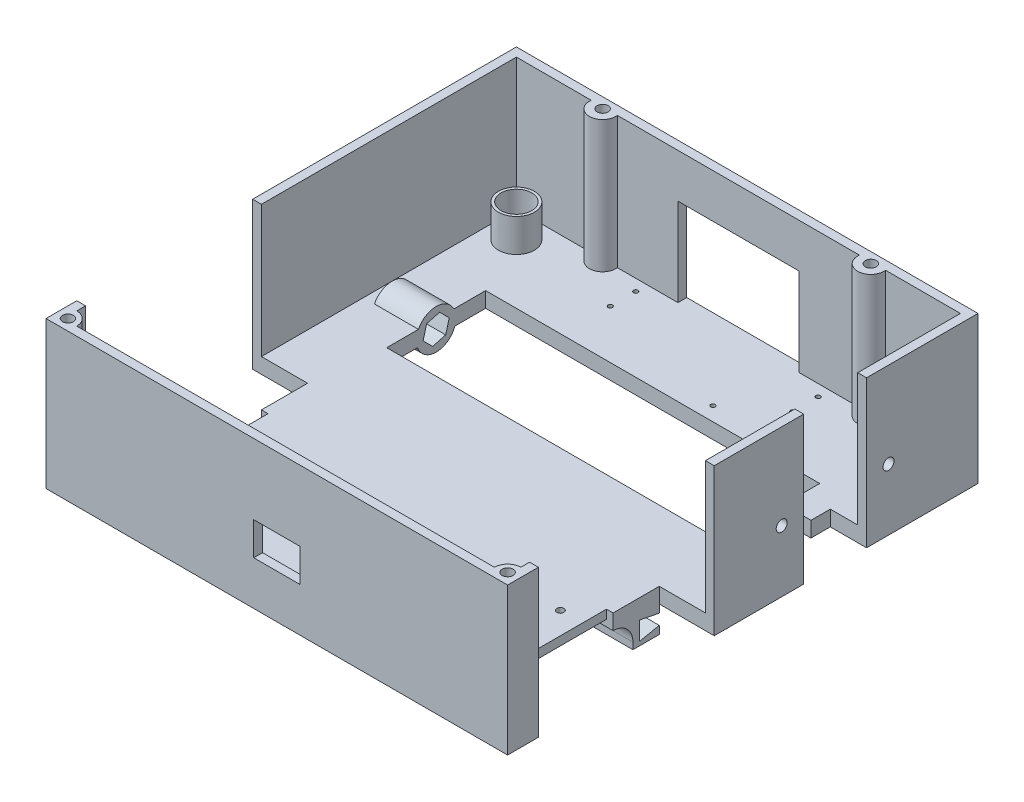
SolidWorks part; units mm, degrees
ref_plane "Front Plane" through (0, 0, 0) normal (0, 0, 1) x (1, 0, 0)
ref_plane "Top Plane" through (0, 0, 0) normal (0, 1, 0) x (1, 0, 0)
ref_plane "Right Plane" through (0, 0, 0) normal (1, 0, 0) x (0, 0, -1)
sketch "Sketch1" plane through (0, 0, 0) normal (0, 1, 0) x (1, 0, 0)
  line L1 (0, 0) -> (210, 0)
  line L2 (0, 0) -> (0, 214)
  line L3 (0, 214) -> (210, 214)
  line L4 (210, 0) -> (210, 214)
  dimension "D1" = 214
  dimension "D2" = 210
extrude "Boss-Extrude1" add sketch "Sketch1" along normal blind 7
sketch "Sketch2" plane through (0, 7, 0) normal (0, 1, 0) x (1, 0, 0)
  line L1 (0, 214) -> (210, 214)
  line L2 (0, 214) -> (0, 0)
  line L3 (0, 0) -> (210, 0)
  line L4 (210, 214) -> (210, 0)
  line L5 (206, 4) -> (4, 4)
  line L6 (206, 4) -> (206, 210)
  line L7 (206, 210) -> (4, 210)
  line L8 (4, 4) -> (4, 210)
  dimension "D1" = 4
  dimension "D2" = 4
  dimension "D3" = 4
  dimension "D4" = 4
extrude "Boss-Extrude2" add sketch "Sketch2" along normal blind 60
sketch "Sketch3" plane through (0, 7, 0) normal (0, 1, 0) x (1, 0, 0)
  line L0 (4, 210) -> (4, 4) construction
  line L1 (206, 4) -> (206, 210) construction
  line L2 (0, 0) -> (210, 0) construction
  circle A0 centre (38, 62) radius 1.6
  circle A1 centre (38, 46) radius 1.6
  circle A2 centre (52, 62) radius 1.6
  circle A3 centre (52, 46) radius 1.6
  circle A4 centre (172, 62) radius 1.6
  circle A5 centre (172, 46) radius 1.6
  circle A6 centre (158, 62) radius 1.6
  circle A7 centre (158, 46) radius 1.6
  dimension "D1" = 3.2
  dimension "D2" = 3.2
  dimension "D3" = 3.2
  dimension "D4" = 3.2
  dimension "D5" = 3.2
  dimension "D6" = 3.2
  dimension "D7" = 3.2
  dimension "D8" = 3.2
  dimension "D16" = 14
  dimension "D17" = 34
  dimension "D18" = 34
  dimension "D19" = 46
  dimension "D9" = 16
  dimension "D10" = 16
  dimension "D11" = 14
  dimension "D12" = 14
  dimension "D13" = 16
  dimension "D14" = 16
  dimension "D15" = 14
  dimension "D20" = 46
extrude "Cut-Extrude1" cut sketch "Sketch3" against normal through all
sketch "Sketch4" plane through (0, 0, 0) normal (0, -1, 0) x (-1, 0, 0)
  line L0 (0, 214) -> (0, 0) construction
  line L1 (0, 14) -> (-25, 14)
  line L2 (0, 14) -> (0, 94)
  line L3 (0, 94) -> (-25, 94)
  line L4 (-25, 14) -> (-25, 94)
  line L5 (-210, 0) -> (-210, 214) construction
  line L6 (-210, 14) -> (-185, 14)
  line L7 (-210, 14) -> (-210, 94)
  line L8 (-210, 94) -> (-185, 94)
  line L9 (-185, 14) -> (-185, 94)
  line L10 (0, 0) -> (-210, 0) construction
  dimension "D1" = 14
  dimension "D2" = 25
  dimension "D3" = 80
  dimension "D4" = 14
  dimension "D5" = 25
  dimension "D6" = 80
extrude "Cut-Extrude2" cut sketch "Sketch4" against normal blind 67
sketch "Sketch5" plane through (0, 0, 0) normal (0, -1, 0) x (-1, 0, 0)
  line L0 (-25, 94) -> (-25, 14) construction
  line L1 (-25, 35) -> (-67, 35)
  line L2 (-25, 35) -> (-25, 73)
  line L3 (-25, 73) -> (-67, 73)
  line L4 (-67, 35) -> (-67, 73)
  line L5 (-185, 14) -> (-185, 94) construction
  line L6 (-185, 35) -> (-143, 35)
  line L7 (-185, 35) -> (-185, 73)
  line L8 (-185, 73) -> (-143, 73)
  line L9 (-143, 35) -> (-143, 73)
  line L10 (-25, 94) -> (-25, 14) construction
  point P12 (-185, 54)
  point P13 (-185, 54)
  point P14 (-25, 54)
  point P17 (-25, 54)
  dimension "D1" = 42
  dimension "D2" = 38
  dimension "D3" = 38
  dimension "D4" = 42
  dimension "D5" = 0
  dimension "D6" = 0
extrude "Cut-Extrude3" cut sketch "Sketch5" against normal blind 3
sketch "Sketch6" plane through (0, 3, 0) normal (0, -1, 0) x (1, 0, 0)
  line L0 (25, -73) -> (67, -73) construction
  line L1 (25, -35) -> (28, -35)
  line L2 (25, -35) -> (25, -73)
  line L3 (25, -73) -> (28, -73)
  line L4 (28, -35) -> (28, -73)
  line L5 (143, -73) -> (185, -73) construction
  line L6 (185, -35) -> (182, -35)
  line L7 (185, -35) -> (185, -73)
  line L8 (185, -73) -> (182, -73)
  line L9 (182, -35) -> (182, -73)
  dimension "D1" = 3
  dimension "D2" = 3
extrude "Cut-Extrude4" cut sketch "Sketch6" against normal through all
sketch "Sketch7" plane through (0, 7, 0) normal (0, 1, 0) x (1, 0, 0)
  line L0 (0, 214) -> (0, 94) construction
  line L1 (29, 171) -> (181, 171)
  line L2 (29, 171) -> (29, 126)
  line L3 (29, 126) -> (181, 126)
  line L4 (181, 171) -> (181, 126)
  line L5 (4, 94) -> (25, 94) construction
  point P4 (105, 171)
  dimension "D1" = 45
  dimension "D2" = 152
  dimension "D3" = 105
  dimension "D4" = 32
extrude "Cut-Extrude5" cut sketch "Sketch7" against normal through all
sketch "Sketch8" plane through (29, 0, 0) normal (1, 0, 0) x (0, 0, -1)
  line L2 (171, 0) -> (171, 7) construction
  line L5 (171, 7) -> (126, 7) construction
  circle A0 centre (148.5, 3) radius 9
  point P2 (148.5, 7)
  point P3 (147.9297, 2.7672)
  point P8 (147.2206, 7)
  point P9 (118.3317, 19.925)
  dimension "D1" = 18
  dimension "D2" = 22.5
  dimension "D3" = 4
extrude "Boss-Extrude3" add sketch "Sketch8" against normal blind 20
sketch "Sketch9" plane through (0, 7, 0) normal (0, 1, 0) x (1, 0, 0)
  line L0 (181, 126) -> (181, 171) construction
  line L1 (181, 154.5) -> (193.5, 154.5)
  line L2 (181, 154.5) -> (181, 142.5)
  line L3 (181, 142.5) -> (193.5, 142.5)
  line L4 (193.5, 154.5) -> (193.5, 142.5)
  line L5 (181, 171) -> (29, 171) construction
  point P8 (193.5, 148.5)
  dimension "D1" = 12.5
  dimension "D2" = 22.5
  dimension "D3" = 12
extrude "Cut-Extrude6" cut sketch "Sketch9" against normal blind 20
sketch "Sketch10" plane through (0, 0, 0) normal (0, -1, 0) x (1, 0, 0)
  line L1 (25, -94) -> (185, -94)
  line L2 (25, -94) -> (25, -82)
  line L3 (25, -82) -> (185, -82)
  line L4 (185, -94) -> (185, -82)
  dimension "D1" = 12
extrude "Boss-Extrude4" add sketch "Sketch10" along normal blind 12
sketch "Sketch11" plane through (25, 0, 0) normal (-1, 0, 0) x (0, 0, 1)
  line L0 (-94, -12) -> (-94, 0) construction
  line L1 (-94, -3.6) -> (-85, -3.6)
  line L2 (-94, -3.6) -> (-94, -8.4)
  line L3 (-94, -8.4) -> (-85, -8.4)
  line L4 (-85, -3.6) -> (-85, -8.4)
  line L5 (-214, 0) -> (-94, 0) construction
  line L6 (-82, -12) -> (-94, -12) construction
  line L7 (-85, -3.6) -> (-85, -1.8)
  line L8 (-85, -1.8) -> (-94, -3.6)
  line L9 (-85, -8.4) -> (-85, -10.2)
  line L10 (-85, -10.2) -> (-94, -8.4)
  line M8 (-94, 0) -> (-94, -12)
  dimension "D1" = 3.6
  dimension "D2" = 3.6
  dimension "D3" = 1.8
  dimension "D4" = 1.8
  dimension "D5" = 9
extrude "Cut-Extrude7" cut sketch "Sketch11" against normal through all contours L4 L1 L3 M8 | L7 L8 L1 | L10 L9 L3
fillet "Fillet1" radius 9 1 edges at (105, 0, -82)
sketch "Sketch12" plane through (0, 7, 0) normal (0, 1, 0) x (1, 0, 0)
  line L0 (4, 210) -> (4, 94) construction
  line L1 (206, 210) -> (4, 210) construction
  line L2 (206, 210) -> (4, 210) construction
  line L3 (206, 4) -> (206, 14) construction
  circle A0 centre (16, 198) radius 7
  circle A1 centre (16, 198) radius 8.2
  circle A2 centre (194, 198) radius 7
  circle A3 centre (194, 198) radius 8.2
  point P14 (127.9483, 216.8969)
  dimension "D1" = 12
  dimension "D3" = 12
  dimension "D2" = 12
  dimension "D4" = 12
extrude "Boss-Extrude5" add sketch "Sketch12" along normal blind 15
sketch "Sketch13" plane through (0, 7, 0) normal (0, 1, 0) x (1, 0, 0)
  circle A0 centre (16, 198) radius 7
  circle A1 centre (194, 198) radius 7
extrude "Cut-Extrude8" cut sketch "Sketch13" against normal blind 12
sketch "Sketch14" plane through (0, 0, 0) normal (0, -1, 0) x (1, 0, 0)
  line L0 (210, -94) -> (210, -214) construction
  line L1 (193.5, -134.6919) -> (210, -134.6919)
  line L2 (193.5, -134.6919) -> (193.5, -163.2919)
  line L3 (193.5, -163.2919) -> (210, -163.2919)
  line L4 (210, -134.6919) -> (210, -163.2919)
  dimension "D1" = 28.6
extrude "Cut-Extrude9" cut sketch "Sketch14" against normal through all
sketch "Sketch15" plane through (0, 0, 0) normal (0, 0, 1) x (1, 0, 0)
  line L0 (210, 67) -> (210, 0) construction
  line L1 (94.5, 35) -> (115.5, 35)
  line L2 (94.5, 35) -> (94.5, 20)
  line L3 (94.5, 20) -> (115.5, 20)
  line L4 (115.5, 35) -> (115.5, 20)
  line L6 (0, 0) -> (210, 0) construction
  point P4 (105, 35)
  dimension "D1" = 105
  dimension "D2" = 15
  dimension "D3" = 21
  dimension "D4" = 20
extrude "Cut-Extrude10" cut sketch "Sketch15" against normal blind 30
sketch "Sketch16" plane through (29, 0, 0) normal (1, 0, 0) x (0, 0, -1)
  line L1 (154.4463, 4.5698) -> (150.1137, 8.9345)
  line L2 (150.1137, 8.9345) -> (144.1674, 7.3647)
  line L3 (144.1674, 7.3647) -> (142.5537, 1.4302)
  line L4 (142.5537, 1.4302) -> (146.8863, -2.9345)
  line L5 (146.8863, -2.9345) -> (152.8326, -1.3647)
  line L6 (152.8326, -1.3647) -> (154.4463, 4.5698)
  circle A0 centre (148.5, 3) radius 5.3261 construction
  dimension "D1" = 6.15
extrude "Cut-Extrude11" cut sketch "Sketch16" against normal blind 10
sketch "Sketch17" plane through (0, 67, 0) normal (0, 1, 0) x (1, 0, 0)
  circle A0 centre (4, 4) radius 6
  circle A1 centre (206, 4) radius 6
  dimension "D1" = 12
  dimension "D2" = 12
extrude "Boss-Extrude6" add sketch "Sketch17" against normal up to next
sketch "Sketch18" plane through (0, 67, 0) normal (0, 1, 0) x (1, 0, 0)
  line L0 (0, 0) -> (210, 0) construction
  line L1 (0, 14) -> (0, 0) construction
  line L2 (210, 0) -> (210, 14) construction
  circle A0 centre (5, 5) radius 2.5
  circle A1 centre (205, 5) radius 2.5
  dimension "D1" = 5
  dimension "D3" = 5
  dimension "D4" = 5
  dimension "D2" = 5
extrude "Cut-Extrude12" cut sketch "Sketch18" against normal up to next
sketch "Sketch21" plane through (0, 0, 0) normal (0, -1, 0) x (-1, 0, 0)
  circle A0 centre (-16, 198) radius 43
  circle A1 centre (-194, 198) radius 43
  dimension "D1" = 86
  dimension "D2" = 86
sketch "Sketch22" plane through (0, 67, 0) normal (0, 1, 0) x (1, 0, 0)
  line L0 (4, 210) -> (4, 94) construction
  line L2 (206, 163.2919) -> (206, 210) construction
  line L3 (0, 0) -> (210, 0) construction
  circle A0 centre (43.99, 209.23) radius 6
  circle A1 centre (166.01, 209.23) radius 6
  dimension "D1" = 39.99
  dimension "D2" = 209.23
  dimension "D3" = 39.99
  dimension "D4" = 209.23
  dimension "D5" = 12
  dimension "D6" = 12
extrude "Boss-Extrude7" add sketch "Sketch22" against normal up to next
sketch "Sketch23" plane through (0, 67, 0) normal (0, 1, 0) x (1, 0, 0)
  circle A0 centre (43.99, 209.23) radius 2.5
  circle A1 centre (166.01, 209.23) radius 2.5
extrude "Cut-Extrude14" cut sketch "Sketch23" against normal up to next
sketch "Sketch24" plane through (0, 0, 0) normal (0, -1, 0) x (-1, 0, 0)
  line L0 (-210, 214) -> (0, 214) construction
  line L1 (0, 214) -> (0, 94) construction
  line L2 (-210, 163.2919) -> (-210, 214) construction
  circle A0 centre (-63.5, 199) radius 5.798
  circle A1 centre (-63.5, 193.202) radius 3
  circle A2 centre (-63.5, 204.798) radius 3
  circle A3 centre (-146.5, 199) radius 5.798
  circle A4 centre (-146.5, 193.202) radius 3
  circle A5 centre (-146.5, 204.798) radius 3
  point P6 (-63.5019, 199.798)
  dimension "D1" = 15
  dimension "D2" = 15
  dimension "D3" = 63.5
  dimension "D4" = 63.5
extrude "Cut-Extrude15" cut sketch "Sketch24" against normal blind 3 contours A2 A0 A1 | A0 A2 | A0 A2 | A0 A1 | A0 A1 | A3 A5 | A3 A5 | A5 A3 A4 | A3 A4 | A3 A4
sketch "Sketch25" plane through (0, 3, 0) normal (0, -1, 0) x (-1, 0, 0)
  circle A0 centre (-146.5, 204.798) radius 1
  circle A1 centre (-146.5, 193.202) radius 1
  circle A2 centre (-63.5, 193.202) radius 1
  circle A3 centre (-63.5, 204.798) radius 1
extrude "Cut-Extrude16" cut sketch "Sketch25" against normal through all
sketch "Sketch27" plane through (0, 0, -210) normal (0, 0, 1) x (1, 0, 0)
  line L0 (160.0596, 7) -> (49.9404, 7) construction
  line L1 (75, 7) -> (135, 7)
  line L2 (75, 7) -> (75, 47)
  line L3 (75, 47) -> (135, 47)
  line L4 (135, 7) -> (135, 47)
  line L5 (4, 67) -> (4, 7) construction
  point P6 (105, 47)
  dimension "D1" = 40
  dimension "D2" = 60
  dimension "D3" = 101
sketch "Sketch29" plane through (0, 0, -210) normal (0, 0, 1) x (1, 0, 0)
  line L0 (160.0596, 7) -> (49.9404, 7) construction
  line L1 (77.5, 7) -> (132.5, 7)
  line L2 (77.5, 7) -> (77.5, 47)
  line L3 (77.5, 47) -> (132.5, 47)
  line L4 (132.5, 7) -> (132.5, 47)
  line L5 (4, 67) -> (4, 7) construction
  point P6 (105, 47)
  dimension "D1" = 40
  dimension "D2" = 55
  dimension "D3" = 101
extrude "Cut-Extrude17" cut sketch "Sketch29" against normal blind 17
sketch "Sketch30" plane through (0, 7, 0) normal (0, 1, 0) x (1, 0, 0)
  circle A0 centre (126.0334, 177.3793) radius 1
  point P2 (126.0334, 177.3793)
extrude "Cut-Extrude18" cut sketch "Sketch30" against normal blind 17
sketch "Sketch31" plane through (210, 0, 0) normal (1, 0, 0) x (0, 0, -1)
  line L0 (134.6919, 67) -> (134.6919, 0) construction
  line L1 (163.2919, 67) -> (163.2919, 0) construction
  line L2 (94, 0) -> (134.6919, 0) construction
  line L3 (155, 0) -> (241, 0) construction
  circle A0 centre (124.6919, 28) radius 2.5
  circle A1 centre (173.2919, 28) radius 2.5
  dimension "D1" = 10
  dimension "D2" = 10
  dimension "D3" = 28
  dimension "D4" = 28
extrude "Cut-Extrude19" cut sketch "Sketch31" against normal blind 17
sketch "Sketch32" plane through (0, 0, 0) normal (0, -1, 0) x (-1, 0, 0)
  line L0 (-210, 214) -> (0, 214) construction
  line L1 (-71, 208.5) -> (-56, 208.5)
  line L2 (-71, 208.5) -> (-71, 189.5)
  line L3 (-71, 189.5) -> (-56, 189.5)
  line L4 (-56, 208.5) -> (-56, 189.5)
  line L5 (-139, 208.5346) -> (-154, 208.5346)
  line L6 (-139, 208.5346) -> (-139, 189.5346)
  line L7 (-139, 189.5346) -> (-154, 189.5346)
  line L8 (-154, 208.5346) -> (-154, 189.5346)
  line L9 (0, 214) -> (0, 94) construction
  line L10 (-210, 163.2919) -> (-210, 214) construction
  point P10 (-63.5, 208.5)
  point P13 (-146.5, 208.5346)
  dimension "D1" = 5.5
  dimension "D2" = 19
  dimension "D3" = 15
  dimension "D4" = 63.5
  dimension "D5" = 15
  dimension "D6" = 19
  dimension "D7" = 63.5
extrude "Cut-Extrude20" cut sketch "Sketch32" against normal blind 3
sketch "Sketch34" plane through (0, 7, 0) normal (0, 1, 0) x (1, 0, 0)
  circle A0 centre (75.5074, 13.9774) radius 1.5
extrude "Cut-Extrude21" cut sketch "Sketch34" against normal through all
